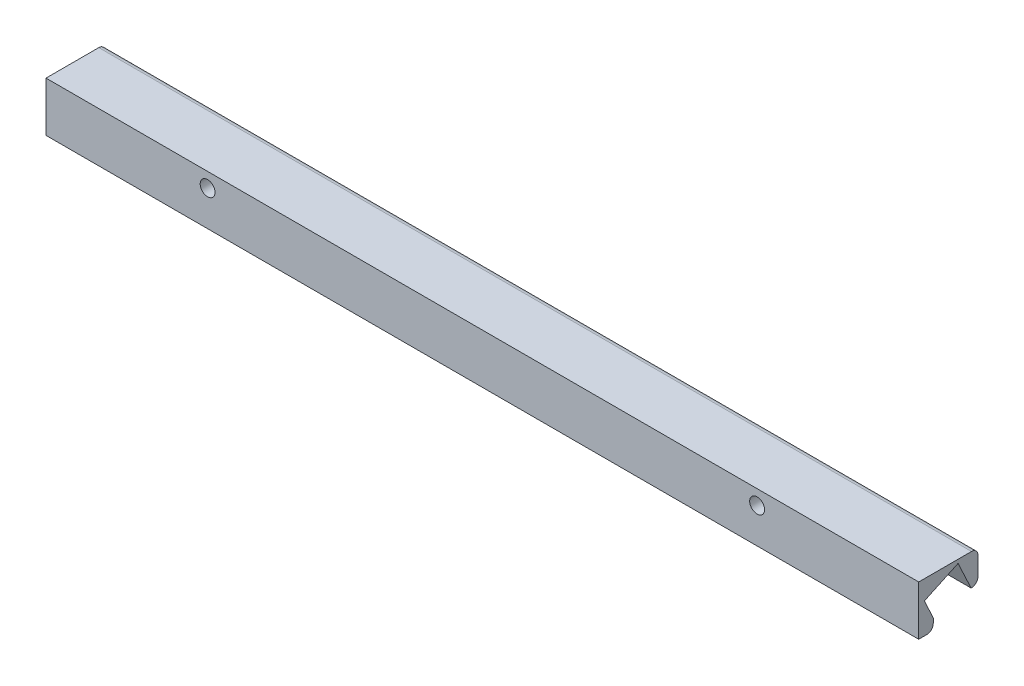
SolidWorks part; units mm, degrees
ref_plane "Front Plane" through (0, 0, 0) normal (0, 0, 1) x (1, 0, 0)
ref_plane "Top Plane" through (0, 0, 0) normal (0, 1, 0) x (1, 0, 0)
ref_plane "Right Plane" through (0, 0, 0) normal (1, 0, 0) x (0, 0, -1)
sketch "Sketch1" plane through (0, 0, 0) normal (1, 0, 0) x (0, 0, -1)
  line L0 (0, 0) -> (2.4995, 0)
  line L2 (18.3407, 7.6355) -> (18.3407, 13.3601)
  line L3 (16.3407, 15.3601) -> (0, 15.3601)
  line L4 (0, 15.3601) -> (0, 0)
  line L6 (16.1904, 5.6412) -> (14.9225, 8.3601)
  line L7 (14.9225, 8.3601) -> (4.5, 3.5)
  line L8 (4.5, 3.5) -> (4.5, 2.0005)
  arc A0 (16.3407, 15.3601) -> (18.3407, 13.3601) centre (16.3407, 13.3601) cw
  arc A1 (16.1904, 5.6412) -> (18.3407, 7.6355) centre (16.3407, 7.6355) ccw
  arc A2 (2.4995, 0) -> (4.5, 2.0005) centre (2.4995, 2.0005) ccw
  dimension "D7" = 4
  dimension "D4" = 4
  dimension "D8" = 4.0011
  dimension "D3" = 11.5
  dimension "D1" = 4.5
  dimension "D5" = 7
  dimension "D6" = 3
extrude "ProfileBoss-Extrude1" add sketch "Sketch1" along normal blind 270
sketch "Sketch2" plane through (0, 1.1513, 0.5368) normal (0, -0.9063, -0.4226) x (1, 0, 0)
  line L0 (270, -5.5575) -> (270, -17.0575) construction
  line L1 (270, -5.5575) -> (0, -5.5575) construction
  line L2 (0, -5.5575) -> (0, -17.0575) construction
  circle A0 centre (36.15, -9.4949) radius 2.3
  circle A1 centre (233.85, -11.3075) radius 2.3
  dimension "D1" = 4.6
  dimension "D3" = 36.15
  dimension "D4" = 5.75
  dimension "D2" = 36.15
extrude "LedStripMountHolesCut-Extrude1" cut sketch "Sketch2" against normal blind 4.5
sketch "Sketch3" plane through (0, 0, 0) normal (0, 0, 1) x (1, 0, 0)
  line L0 (270, 15.3601) -> (270, 0) construction
  line L1 (0, 15.3601) -> (0, 0) construction
  circle A0 centre (50, 10.8601) radius 2.3
  circle A1 centre (220, 10.8601) radius 2.3
  dimension "D1" = 4.6
  dimension "D3" = 50
  dimension "D4" = 4.5
  dimension "D2" = 50
extrude "MountingHolesCut-Extrude3" cut sketch "Sketch3" against normal blind 4.5
sketch "Sketch4" plane through (0, 1.1513, 0.5368) normal (0, -0.9063, -0.4226) x (1, 0, 0)
  line L0 (270, -5.5575) -> (0, -5.5575) construction
  line L1 (242, -5.5575) -> (270, -5.5575)
  line L2 (242, -5.5575) -> (242, -17.0575)
  line L3 (242, -17.0575) -> (270, -17.0575)
  line L4 (270, -5.5575) -> (270, -17.0575)
  line L5 (270, -17.0575) -> (0, -17.0575) construction
  line L6 (0, -5.5575) -> (28, -5.5575)
  line L7 (0, -5.5575) -> (0, -17.0575)
  line L8 (0, -17.0575) -> (28, -17.0575)
  line L9 (28, -5.5575) -> (28, -17.0575)
  dimension "D1" = 28
  dimension "D2" = 28
extrude "PowerConnectorCut-Extrude4" cut sketch "Sketch4" against normal blind 6.5
equation "\"LightStripLength\"= 270mm'From Step file"
equation "\"D1@ProfileBoss-Extrude1\"=\"LightStripLength\""
equation "\"LightStripMountHoleFromLeftOrRightSide\"= ( \"LightStripLength\" - \"LightStripDistanceBetweenMountingHoles\" ) / 2"
equation "\"D3@Sketch2\"=\"LightStripMountHoleFromLeftOrRightSide\""
equation "\"LightStripWidth\"= 11.5mm'Spec"
equation "\"D3@Sketch1\"=\"LightStripWidth\""
equation "\"D4@Sketch2\"=\"LightStripWidth\"/2"
equation "\"D3@Sketch3\"=\"LightStripGuideMountingHoleFromLeftOrRightSide\""
equation "\"D2@Sketch2\"=\"LightStripMountHoleFromLeftOrRightSide\""
equation "\"LightStripGuideMountingHoleFromLeftOrRightSide\"= 50mm"
equation "\"D2@Sketch3\"=\"LightStripGuideMountingHoleFromLeftOrRightSide\""
equation "\"LightStripDistanceBetweenMountingHoles\"= 197.7mm'From Step file"
